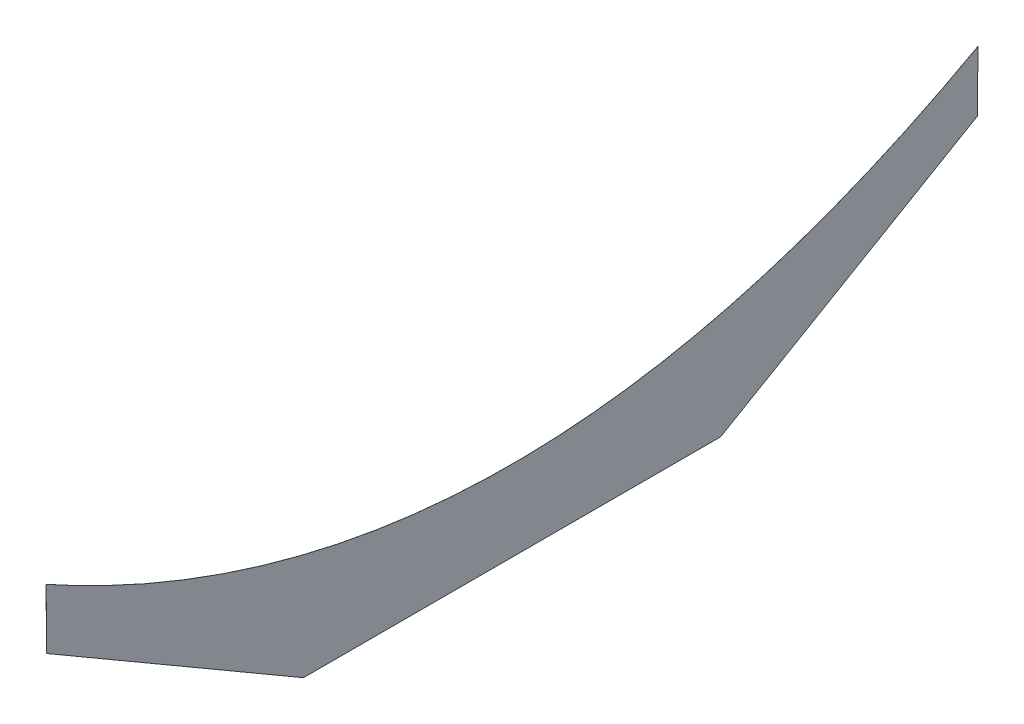
SolidWorks part; units mm, degrees
material "6061 Alloy"
ref_plane "Front Plane" through (0, 0, 0) normal (0, 0, 1) x (1, 0, 0)
ref_plane "Top Plane" through (0, 0, 0) normal (0, 1, 0) x (1, 0, 0)
ref_plane "Right Plane" through (0, 0, 0) normal (1, 0, 0) x (0, 0, -1)
sketch "Sketch1" plane through (0, 0, 0) normal (1, 0, 0) x (0, 0, -1)
  line L1 (734.4071, 124.6761) -> (733.357, 29.7612)
  line L2 (328.7708, -205.5239) -> (733.357, 29.7612)
  line L5 (328.7708, -205.5239) -> (-328.7708, -205.5239)
  line L6 (-328.7708, -205.5239) -> (-733.3571, 29.7612)
  line L7 (-734.4072, 124.6761) -> (-733.3571, 29.7612)
  parabola Q0 (0, -78.5239) -> (734.4071, 124.6761) focus (0, 585.0511) apex (0, -78.5239)
  parabola Q1 (0, -78.5239) -> (-734.4072, 124.6761) focus (0, 585.0511) apex (0, -78.5239)
extrude "Boss-Extrude1" add sketch "Sketch1" along normal blind 0.127
